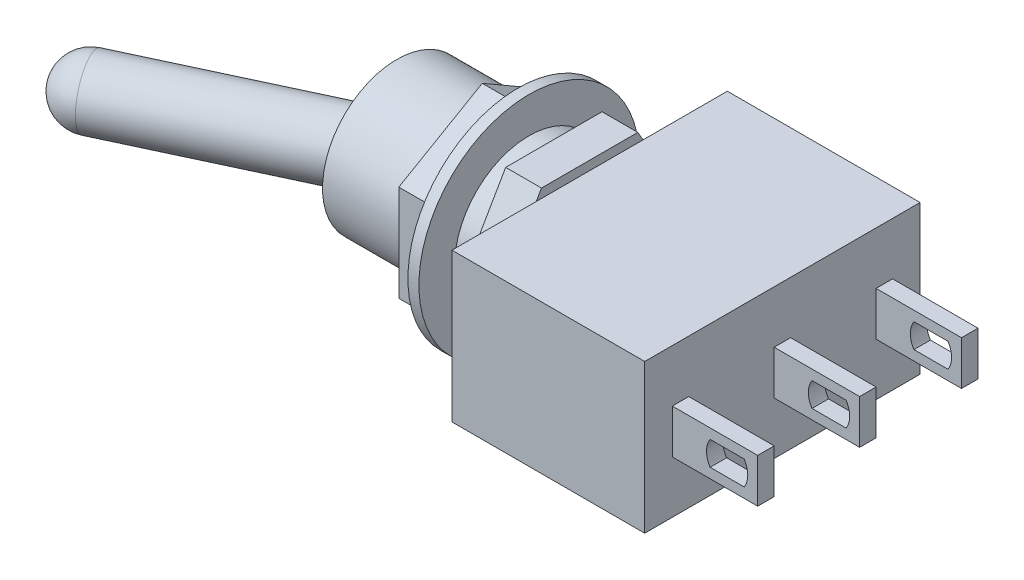
SolidWorks part; units mm, degrees
ref_plane "Front Plane" through (0, 0, 0) normal (0, 0, 1) x (1, 0, 0)
ref_plane "Top Plane" through (0, 0, 0) normal (0, 1, 0) x (1, 0, 0)
ref_plane "Right Plane" through (0, 0, 0) normal (1, 0, 0) x (0, 0, -1)
sketch "Sketch1" plane through (0, 0, 0) normal (0, 0, 1) x (1, 0, 0)
  line L0 (0, 0) -> (85.4969, 0) construction
  line L1 (0, 3.43) -> (8.89, 3.43)
  line L2 (0, 3.43) -> (0, -3.43)
  line L3 (0, -3.43) -> (8.89, -3.43)
  line L4 (8.89, 3.43) -> (8.89, -3.43)
  dimension "D1" = 8.89
  dimension "D2" = 6.86
extrude "Extrude1" add sketch "Sketch1" along normal mid plane 12.7
sketch "Sketch2" plane through (0, 0, 0) normal (-1, 0, 0) x (0, 0, 1)
  circle A0 centre (0, 0) radius 3.43
  dimension "D1" = 6.86
extrude "Extrude2" add sketch "Sketch2" along normal blind 8.89
sketch "Sketch4" plane through (-8.89, 0, 0) normal (-1, 0, 0) x (0, 0, 1)
  circle A0 centre (0, 0) radius 2.5
  dimension "D1" = 5
extrude "Extrude3" cut sketch "Sketch4" against normal blind 0.5
sketch "Sketch3" plane through (0, 0, 0) normal (0, 1, 0) x (1, 0, 0)
  line L0 (-8.89, -0.6145) -> (-17.6903, -4.7181) construction
  line L1 (-8.89, 3.43) -> (-8.89, -3.43) construction
  line L2 (0, -6.35) -> (0, 0) construction
  line L3 (-6.5, 0.5) -> (-5.883, -0.8232)
  line L4 (-5.883, -0.8232) -> (-17.483, -6.2324)
  line L5 (8.89, 6.35) -> (0, 6.35) construction
  line L6 (-19.4232, -5.5262) -> (-6.5, 0.5)
  line L7 (-19.5952, 0) -> (0, 0) construction
  line L8 (-15.89, -7.3593) -> (-15.89, 0) construction
  arc A0 (-19.4232, -5.5262) -> (-17.483, -6.2324) centre (-18.1, -4.9092) ccw
  point P15 (-7.5723, 0)
  point P19 (-8.89, 0)
  point P20 (-15.89, -5.4896)
  point P21 (0, 0)
  dimension "D4" = 10.67
  dimension "D1" = 25
  dimension "D2" = 2.92
  dimension "D3" = 0.5
  dimension "D5" = 6.5
  dimension "D6" = 7
  dimension "D7" = 1.3177
  dimension "D8" = 5.4896
revolve "Revolve3" add sketch "Sketch3" angle 360 about L0
sketch "Sketch5" plane through (8.89, 0, 0) normal (1, 0, 0) x (0, 0, -1)
  line L0 (0, 0) -> (-9.9291, 0) construction
  line L1 (-5.08, 1.015) -> (-4.32, 1.015)
  line L2 (-5.08, 1.015) -> (-5.08, -1.015)
  line L3 (-5.08, -1.015) -> (-4.32, -1.015)
  line L4 (-4.32, 1.015) -> (-4.32, -1.015)
  line L5 (-4.7, 1.015) -> (-4.7, -2.3382) construction
  dimension "D1" = 4.7
  dimension "D2" = 0.76
  dimension "D3" = 2.03
extrude "Extrude4" add sketch "Sketch5" along normal blind 3.94
pattern_linear "LPattern1" count 3 spacing 4.7 along (0, 0, -1) of "Extrude4"
sketch "Sketch6" plane through (0, 0, 5.08) normal (0, 0, 1) x (1, 0, 0)
  line L0 (12.83, 1.015) -> (12.83, -1.015) construction
  line L3 (12.83, 0.5578) -> (8.89, 0.5578)
  line L4 (12.2058, 0.5578) -> (10.6348, 0.5578)
  line L6 (12.83, -0.5578) -> (8.89, -0.5578)
  line L7 (12.2058, -0.5578) -> (10.6348, -0.5578)
  arc A0 (12.2058, -0.5578) -> (12.2058, 0.5578) centre (11.3578, 0) ccw
  arc A1 (10.6348, -0.5578) -> (10.6348, 0.5578) centre (11.4828, 0) cw
  dimension "D3" = 1.015
  dimension "D4" = 1.015
  dimension "D7" = 1.4722
  dimension "D8" = 0.125
  dimension "D5" = 0.5578
  dimension "D6" = 0.5578
  dimension "D1" = 0.4572
  dimension "D2" = 0.4572
extrude "Cut-Extrude1" cut sketch "Sketch6" against normal through all
sketch "Sketch7" plane through (0, 0, 0) normal (-1, 0, 0) x (0, 0, 1)
  line L1 (-4.4434, 0) -> (-2.2217, -3.8481)
  line L2 (-2.2217, -3.8481) -> (2.2217, -3.8481)
  line L3 (2.2217, -3.8481) -> (4.4434, 0)
  line L4 (4.4434, 0) -> (2.2217, 3.8481)
  line L5 (2.2217, 3.8481) -> (-2.2217, 3.8481)
  line L6 (-2.2217, 3.8481) -> (-4.4434, 0)
  circle A0 centre (0, 0) radius 3.8481 construction
  dimension "D1" = 7.6962
extrude "Boss-Extrude1" add sketch "Sketch7" along normal blind 1.651
sketch "Sketch8" plane through (0, 0, 0) normal (0, 1, 0) x (1, 0, 0)
  line L0 (-1.651, -4.4434) -> (-1.651, -2.2217) construction
  line L1 (-2.794, 0) -> (-3.302, 0)
  line L2 (-2.794, 0) -> (-2.794, -5.08)
  line L3 (-2.794, -5.08) -> (-3.302, -5.08)
  line L4 (-3.302, 0) -> (-3.302, -5.08)
  dimension "D1" = 0.508
  dimension "D2" = 5.08
  dimension "D3" = 5.08
  dimension "D4" = 1.143
revolve "Revolve4" add sketch "Sketch8" angle 360 about L1
sketch "Sketch9" plane through (-3.302, 0, 0) normal (-1, 0, 0) x (0, 0, 1)
  line L1 (0, 4.4434) -> (-3.8481, 2.2217)
  line L2 (-3.8481, 2.2217) -> (-3.8481, -2.2217)
  line L3 (-3.8481, -2.2217) -> (0, -4.4434)
  line L4 (0, -4.4434) -> (3.8481, -2.2217)
  line L5 (3.8481, -2.2217) -> (3.8481, 2.2217)
  line L6 (3.8481, 2.2217) -> (0, 4.4434)
  circle A0 centre (0, 0) radius 4.4434 construction
  dimension "D1" = 7.6962
extrude "Boss-Extrude2" add sketch "Sketch9" along normal blind 1.651
